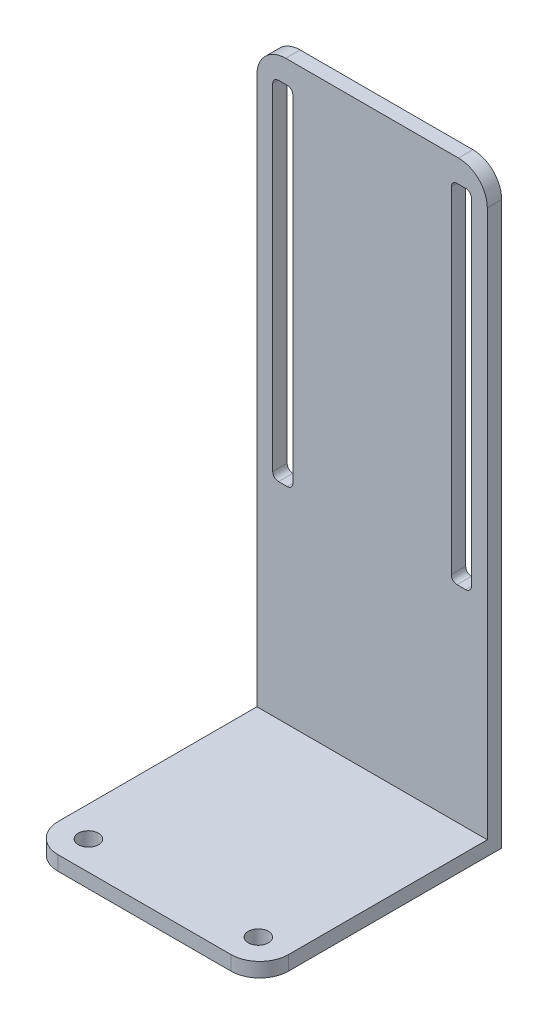
SolidWorks part; units mm, degrees
ref_plane "Front Plane" through (0, 0, 0) normal (0, 0, 1) x (1, 0, 0)
ref_plane "Top Plane" through (0, 0, 0) normal (0, 1, 0) x (1, 0, 0)
ref_plane "Right Plane" through (0, 0, 0) normal (1, 0, 0) x (0, 0, -1)
sketch "Sketch1" plane through (0, 0, 0) normal (0, 1, 0) x (1, 0, 0)
  line L0 (0, 21) -> (0, -21.5902) construction
  line L1 (20, 21) -> (-20, 21)
  line L2 (20, 21) -> (20, -16)
  line L3 (15, -21) -> (-15, -21)
  line L4 (-20, 21) -> (-20, -16)
  line L5 (20, 21) -> (-20, -21) construction
  line L6 (20, -21) -> (-20, 21) construction
  line L7 (-20, -21) -> (-20, -16)
  line L8 (-20, -16) -> (20, -16) construction
  line L9 (14.75, -16) -> (-14.75, -16) construction
  circle A0 centre (14.75, -16) radius 1.75
  circle A1 centre (-14.75, -16) radius 1.75
  arc A2 (20, -16) -> (15, -21) centre (15, -16) cw
  arc A3 (-15, -21) -> (-20, -16) centre (-15, -16) cw
  point P0 (0, 0)
  point P13 (0, -16)
  dimension "D5" = 3.5
  dimension "D6" = 5
  dimension "D1" = 40
  dimension "D2" = 42
  dimension "D3" = 5
  dimension "D4" = 29.5
extrude "Boss-Extrude1" add sketch "Sketch1" along normal blind 2.5 contours A2 L2 L1 L4 A3 L3 | A1 | A0
sketch "Sketch2" plane through (0, 2.5, 0) normal (0, 1, 0) x (1, 0, 0)
  line L0 (-20, 21) -> (-20, 18.5)
  line L1 (-20, 21) -> (-20, -16) construction
  line L2 (-20, 18.5) -> (20, 18.5)
  line L3 (20, 21) -> (20, -16) construction
  line L4 (20, 18.5) -> (20, 21)
  line L5 (20, 21) -> (-20, 21)
  dimension "D1" = 2.5
extrude "Boss-Extrude2" add sketch "Sketch2" along normal blind 100
fillet "Fillet1" radius 5 2 edges at (20, 102.5, -19.75) (-20, 102.5, -19.75)
sketch "Sketch3" plane through (0, 0, -18.5) normal (0, 0, 1) x (1, 0, 0)
  line L0 (20, 92.6329) -> (15.5, 92.6329) construction
  line L1 (20, 97.5) -> (20, 0) construction
  line L2 (-20, 92.6329) -> (-15.5, 92.6329) construction
  line L3 (-20, 97.5) -> (-20, 0) construction
  line L4 (13.75, 92.6329) -> (17.25, 92.6329) construction
  line L5 (17.25, 92.6329) -> (17.25, 39.2352)
  line L6 (17.25, 92.6329) -> (17.25, 97.5564)
  line L7 (16.25, 98.5564) -> (14.75, 98.5564)
  line L8 (13.75, 97.5564) -> (13.75, 39.2352)
  line L9 (14.75, 38.2352) -> (16.25, 38.2352)
  line L10 (0, 102.5) -> (0, 20.8477) construction
  line L11 (15, 102.5) -> (-15, 102.5) construction
  line L12 (-13.75, 92.6329) -> (-17.25, 92.6329) construction
  line L13 (-20, 92.6329) -> (-15.5, 92.6329) construction
  line L14 (-14.75, 38.2352) -> (-16.25, 38.2352)
  line L15 (-13.75, 97.5564) -> (-13.75, 39.2352)
  line L16 (-16.25, 98.5564) -> (-14.75, 98.5564)
  line L17 (-17.25, 92.6329) -> (-17.25, 97.5564)
  line L18 (-17.25, 92.6329) -> (-17.25, 39.2352)
  arc A0 (17.25, 39.2352) -> (16.25, 38.2352) centre (16.25, 39.2352) cw
  arc A1 (13.75, 39.2352) -> (14.75, 38.2352) centre (14.75, 39.2352) ccw
  arc A2 (14.75, 98.5564) -> (13.75, 97.5564) centre (14.75, 97.5564) ccw
  arc A3 (17.25, 97.5564) -> (16.25, 98.5564) centre (16.25, 97.5564) ccw
  arc A4 (-17.25, 97.5564) -> (-16.25, 98.5564) centre (-16.25, 97.5564) cw
  arc A5 (-14.75, 98.5564) -> (-13.75, 97.5564) centre (-14.75, 97.5564) cw
  arc A6 (-13.75, 39.2352) -> (-14.75, 38.2352) centre (-14.75, 39.2352) cw
  arc A7 (-17.25, 39.2352) -> (-16.25, 38.2352) centre (-16.25, 39.2352) ccw
  point P11 (15.5, 92.6329)
  point P42 (-15.5, 92.6329)
  dimension "D4" = 1
  dimension "D1" = 4.5
  dimension "D3" = 3.5
extrude "Cut-Extrude1" cut sketch "Sketch3" against normal through all
